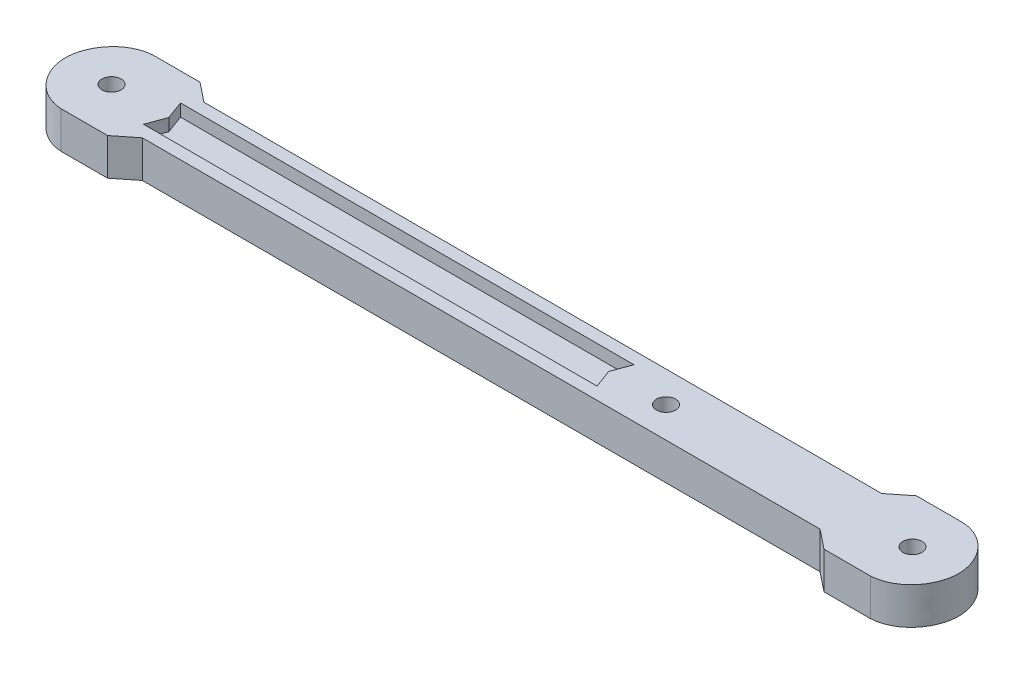
SolidWorks part; units mm, degrees
ref_plane "Plan de face" through (0, 0, 0) normal (0, 0, 1) x (1, 0, 0)
ref_plane "Plan de dessus" through (0, 0, 0) normal (0, 1, 0) x (1, 0, 0)
ref_plane "Plan de droite" through (0, 0, 0) normal (1, 0, 0) x (0, 0, -1)
sketch "Esquisse2" plane through (0, 0, 0) normal (0, 1, 0) x (1, 0, 0)
  line L0 (30, 7.5) -> (-90, 7.5)
  line L1 (-3.3, 0) -> (3.3, 0) construction
  line L2 (30, -7.5) -> (-90, -7.5)
  line L3 (-90, 7.5) -> (-100, 7.5)
  line L4 (-100, 7.5) -> (-100, -7.5)
  line L5 (-100, -7.5) -> (-90, -7.5)
  line L6 (30, 7.5) -> (40, 7.5)
  line L7 (30, -7.5) -> (40, -7.5)
  line L8 (40, 7.5) -> (50, 7.5)
  line L9 (50, 7.5) -> (50, -7.5)
  line L10 (50, -7.5) -> (40, -7.5)
  circle A0 centre (-90, 0) radius 1.55
  circle A1 centre (0, 0) radius 1.55
  circle A2 centre (40, 0) radius 1.55
  dimension "D6" = 3.1
  dimension "D1" = 90
  dimension "D2" = 15
  dimension "D3" = 10
  dimension "D4" = 40
  dimension "D5" = 10
  dimension "D7" = 10
  dimension "D8" = 10
extrude "Boss.-Extru.1" add sketch "Esquisse2" along normal blind 6
sketch "Esquisse3" plane through (0, 0, 0) normal (0, -1, 0) x (1, 0, 0)
  line L0 (-90, -7.5) -> (-83.1409, -7.5)
  line L1 (50, -7.5) -> (-100, -7.5) construction
  line L2 (-83.1409, -7.5) -> (-80, -5)
  line L3 (-80, -5) -> (0, -5)
  line L4 (0, -3.3) -> (0, 3.3) construction
  line L5 (-90, 7.5) -> (-83.1409, 7.5)
  line L6 (-100, 7.5) -> (50, 7.5) construction
  line L7 (-83.1409, 7.5) -> (-80, 5)
  line L8 (-80, 5) -> (0, 5)
  line L9 (40, -7.5) -> (33.1409, -7.5)
  line L10 (60, 17.5) -> (-110, 17.5)
  line L11 (60, 17.5) -> (60, -17.5)
  line L12 (60, -17.5) -> (-110, -17.5)
  line L13 (-110, 17.5) -> (-110, -17.5)
  line L14 (60, 17.5) -> (-110, -17.5) construction
  line L15 (60, -17.5) -> (-110, 17.5) construction
  line L16 (33.1409, -7.5) -> (30, -5)
  line L17 (30, -5) -> (0, -5)
  line L18 (40, 7.5) -> (33.1409, 7.5)
  line L19 (33.1409, 7.5) -> (30, 5)
  line L20 (30, 5) -> (0, 5)
  line L21 (-100, -7.5) -> (-100, 7.5) construction
  line L22 (50, 7.5) -> (50, -7.5) construction
  line L23 (3.3, 0) -> (-3.3, 0) construction
  circle A0 centre (-90, 0) radius 7.5 construction
  circle A1 centre (40, 0) radius 7.5 construction
  spline S0 degree 3 poles (-90, -7.5) (-94.2662, -7.719) (-100.7336, 0.0001) (-94.2667, 7.7185) (-90, 7.5) knots 0 0 0 0 0.500006 1 1 1 1
  spline S1 degree 3 poles (40, -7.5) (44.2929, -7.7071) (50.7071, 0) (44.2929, 7.7071) (40, 7.5) knots 0 0 0 0 0.5 1 1 1 1
  point P23 (-25, 0)
  dimension "D1" = 10
  dimension "D2" = 10
  dimension "D3" = 10
  dimension "D4" = 10
  dimension "D5" = 5
  dimension "D6" = 5
  dimension "D7" = 10
  dimension "D8" = 10
  dimension "D9" = 6.8591
  dimension "D10" = 6.8591
  dimension "D11" = 5.8864
  dimension "D12" = 5.89
  dimension "D13" = 4.11
  dimension "D14" = 4.1136
  dimension "D15" = 2.5
  dimension "D16" = 10
  dimension "D17" = 10
  dimension "D18" = 6.8591
  dimension "D19" = 6.8591
  dimension "D20" = 6
  dimension "D21" = 6
  dimension "D22" = 2.5
extrude "Enlèv. mat.-Extru.1" cut sketch "Esquisse3" against normal blind 10
sketch "Esquisse4" plane through (0, 6, 0) normal (0, 1, 0) x (1, 0, 0)
  line L0 (-81.8, 3) -> (-80.7, 0)
  line L1 (-81.8, 3) -> (-8.2, 3)
  line L2 (-9.3, 0) -> (-8.2, 3)
  line L3 (-3.3, 0) -> (3.3, 0) construction
  line L4 (-9.3, 0) -> (-8.2, -3)
  line L5 (-81.8, -3) -> (-8.2, -3)
  line L6 (-81.8, -3) -> (-80.7, 0)
  line L7 (-80, 5) -> (30, 5) construction
  circle A0 centre (-90, 0) radius 1.55 construction
  dimension "D1" = 8.2
  dimension "D2" = 9.3
  dimension "D3" = 8.2
  dimension "D4" = 9.3
  dimension "D5" = 2
extrude "Enlèv. mat.-Extru.2" cut sketch "Esquisse4" against normal blind 2
